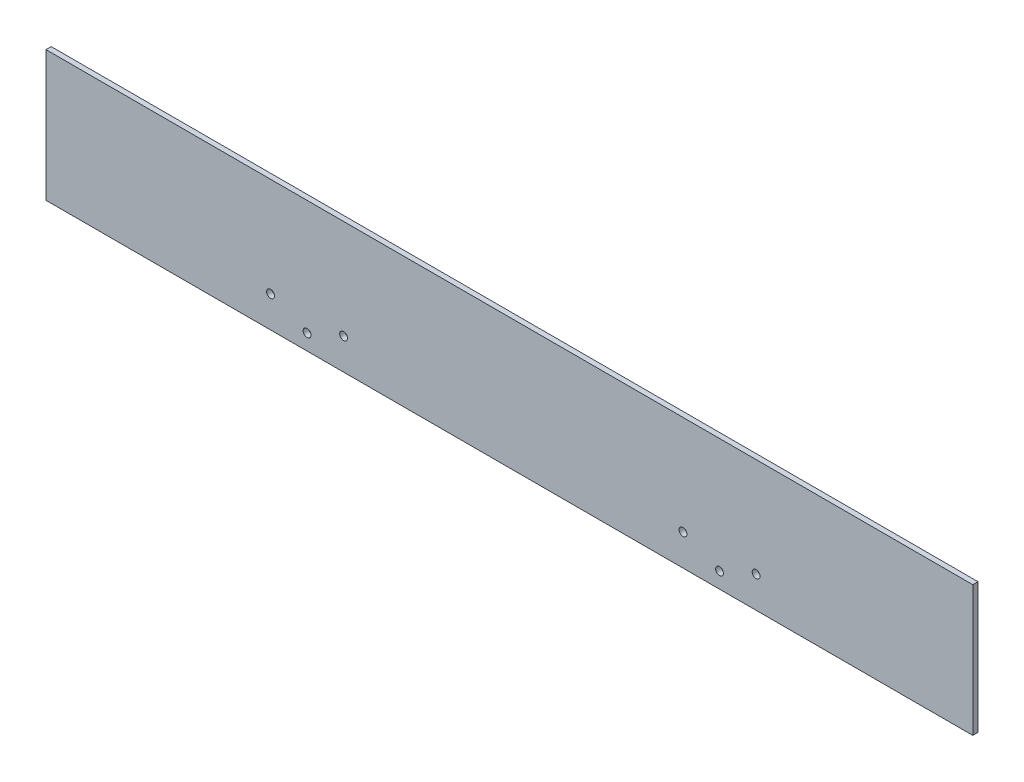
SolidWorks part; units mm, degrees
ref_plane "Plan de face" through (0, 0, 0) normal (0, 0, 1) x (1, 0, 0)
ref_plane "Plan de dessus" through (0, 0, 0) normal (0, 1, 0) x (1, 0, 0)
ref_plane "Plan de droite" through (0, 0, 0) normal (1, 0, 0) x (0, 0, -1)
sketch "Esquisse1" plane through (0, 0, 0) normal (0, 0, 1) x (1, 0, 0)
  line L1 (-177.5, 25) -> (177.5, 25)
  line L2 (-177.5, 25) -> (-177.5, -25)
  line L3 (-177.5, -25) -> (177.5, -25)
  line L4 (177.5, 25) -> (177.5, -25)
  line L5 (-177.5, 25) -> (177.5, -25) construction
  line L6 (-177.5, -25) -> (177.5, 25) construction
  point P0 (0, 0)
  dimension "D1" = 355
  dimension "D2" = 50
extrude "Boss.-Extru.1" add sketch "Esquisse1" along normal blind 2
sketch "Esquisse2" plane through (0, 0, 0) normal (0, 0, -1) x (-1, 0, 0)
  circle A0 centre (-94.5, -13) radius 1.5
  circle A1 centre (-80.5, -19) radius 1.5
  circle A2 centre (-66.5, -13) radius 1.5
  circle A3 centre (77.5, -19) radius 1.5
  circle A4 centre (63.5, -13) radius 1.5
  circle A5 centre (91.5, -13) radius 1.5
extrude "Enlèv. mat.-Extru.1" cut sketch "Esquisse2" against normal through all
